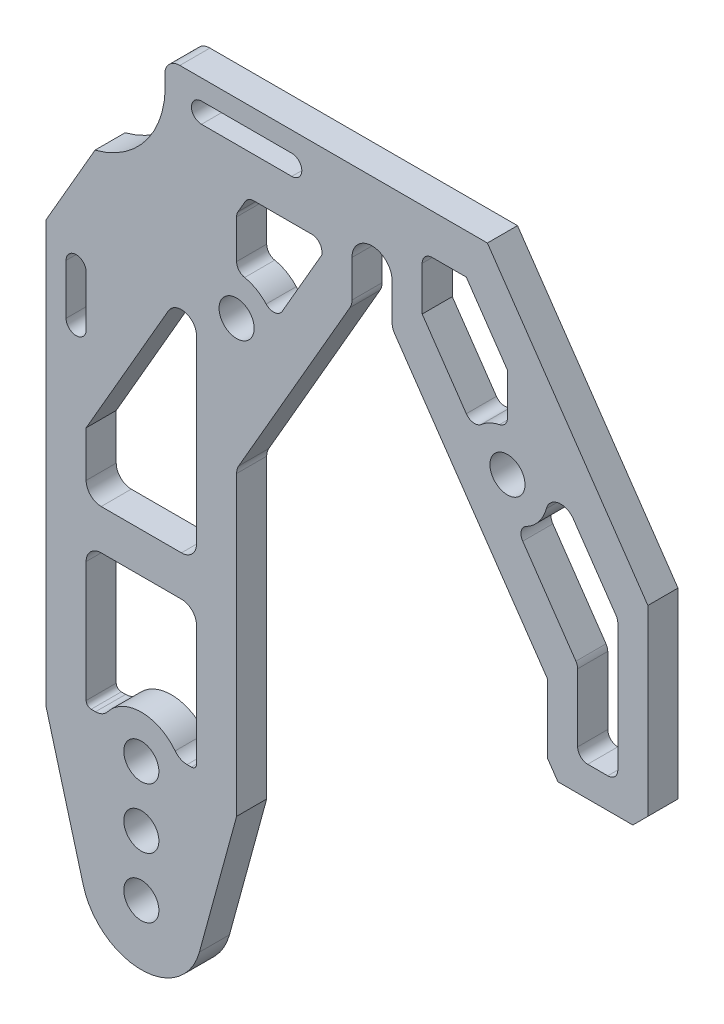
SolidWorks part; units mm, degrees
ref_plane "Plano frontal" through (0, 0, 0) normal (0, 0, 1) x (1, 0, 0)
ref_plane "Plano superior" through (0, 0, 0) normal (0, 1, 0) x (1, 0, 0)
ref_plane "Plano direito" through (0, 0, 0) normal (1, 0, 0) x (0, 0, -1)
sketch "Esboço1" plane through (0, 0, 0) normal (0, 0, 1) x (1, 0, 0)
  line L0 (23.094, 160) -> (88, 160)
  line L3 (100, 142.5303) -> (100, 114)
  line L4 (100, 114) -> (84, 114)
  line L5 (84, 114) -> (69, 135.8372)
  line L6 (69, 135.8372) -> (69, 144)
  line L7 (61, 144) -> (61, 135.8372)
  line L8 (61, 135.8372) -> (38, 96)
  line L9 (38, 96) -> (38, 0)
  line L13 (0, 0) -> (0, 120)
  line L14 (0, 0) -> (38, 0)
  line L15 (100, 142.5303) -> (88, 160)
  line L16 (23.094, 160) -> (0, 120)
  line L17 (19, 36) -> (19, 24) construction
  line L18 (19, 24) -> (19, 12) construction
  line L19 (19, 12) -> (19, 0) construction
  line L20 (41, 154) -> (49, 154) construction
  line L21 (41, 156) -> (49, 156)
  line L22 (41, 152) -> (49, 152)
  line L23 (6, 115) -> (6, 105) construction
  line L24 (8, 115) -> (8, 105)
  line L25 (4, 115) -> (4, 105)
  arc A1 (69, 144) -> (61, 144) centre (65, 144) ccw
  circle A2 centre (19, 12) radius 3.5
  circle A3 centre (19, 24) radius 3.5
  circle A4 centre (19, 36) radius 3.5
  arc A5 (41, 156) -> (41, 152) centre (41, 154) ccw
  arc A6 (49, 152) -> (49, 156) centre (49, 154) ccw
  arc A7 (8, 115) -> (4, 115) centre (6, 115) ccw
  arc A8 (4, 105) -> (8, 105) centre (6, 105) ccw
  circle A9 centre (92, 122) radius 3.5
  circle A10 centre (38, 122) radius 3.5
  point P24 (45, 154)
  point P31 (6, 110)
  dimension "D11" = 7
  dimension "D16" = 2
  dimension "D20" = 2
  dimension "D23" = 7
  dimension "D24" = 8
  dimension "D25" = 8
  dimension "D26" = 7
  dimension "D1" = 160
  dimension "D2" = 100
  dimension "D3" = 8
  dimension "D4" = 46
  dimension "D5" = 16
  dimension "D6" = 35
  dimension "D7" = 16
  dimension "D8" = 46
  dimension "D9" = 150
  dimension "D10" = 12
  dimension "D12" = 96
  dimension "D13" = 120
  dimension "D14" = 12
  dimension "D15" = 6
  dimension "D17" = 20
  dimension "D18" = 8
  dimension "D19" = 6
  dimension "D21" = 10
  dimension "D22" = 110
extrude "Ressalto-extrusão1" add sketch "Esboço1" along normal blind 6
fillet "Filete1" radius 3 5 edges at (38, 96, 3) (61, 135.8372, 3) (69, 135.8372, 3) (84, 114, 3) (100, 114, 3)
chamfer "Chanfro1" distance 2 angle 45 2 edges at (0, 0, 3) (38, 0, 3)
sketch "Esboço2" plane through (0, 0, 6) normal (0, 0, 1) x (1, 0, 0)
  line L0 (75, 152) -> (75, 141.2317)
  line L1 (75, 141.2317) -> (85.2552, 126.3021)
  line L2 (92, 130) -> (92, 140.0473)
  line L3 (92, 140.0473) -> (83.7897, 152)
  line L4 (83.7897, 152) -> (75, 152)
  line L11 (69.5272, 135.0697) -> (83.1061, 115.3014) construction
  line L12 (100, 142.5303) -> (88, 160) construction
  line L13 (88, 160) -> (23.094, 160) construction
  line L14 (100, 117) -> (100, 142.5303) construction
  line L15 (69, 144) -> (69, 136.7683) construction
  line L16 (65, 140) -> (65, 160) construction
  line L19 (38, 130) -> (38, 140.0473)
  line L20 (55, 141.4449) -> (45.4526, 124.9083)
  line L21 (55, 144) -> (55, 141.4449)
  line L22 (38, 140.0473) -> (40.2821, 144)
  line L23 (40.2821, 144) -> (55, 144)
  line L24 (41, 152) -> (49, 152) construction
  line L25 (38.4019, 96.6962) -> (60.5981, 135.141) construction
  line L26 (61, 136.641) -> (61, 144) construction
  arc A4 (92, 130) -> (85.2552, 126.3021) centre (92, 122) ccw
  arc A5 (69, 144) -> (61, 144) centre (65, 144) ccw construction
  arc A6 (38, 130) -> (45.4526, 124.9083) centre (38, 122) cw
  dimension "D6" = 8
  dimension "D1" = 8
  dimension "D2" = 8
  dimension "D3" = 8
  dimension "D4" = 8
  dimension "D5" = 6
  dimension "D7" = 8
  dimension "D8" = 8
  dimension "D9" = 6
extrude "Corte-extrusão1" cut sketch "Esboço2" against normal blind 6
sketch "Esboço3" plane through (0, 0, 6) normal (0, 0, 1) x (1, 0, 0)
  line L0 (100, 142.5303) -> (120, 113.414)
  line L1 (100, 117) -> (100, 142.5303) construction
  line L2 (100, 142.5303) -> (88, 160) construction
  line L3 (83.1061, 115.3014) -> (100, 90.707)
  line L4 (69.5272, 135.0697) -> (83.1061, 115.3014) construction
  line L5 (120, 113.414) -> (120, 77)
  line L6 (100, 90.707) -> (100, 77)
  line L7 (100, 77) -> (102.0607, 74)
  line L8 (102.0607, 74) -> (117, 74)
  line L9 (117, 74) -> (120, 77)
  line L10 (85.5789, 114) -> (97, 114) construction
  line L11 (83.1061, 115.3014) -> (100, 117)
  line L12 (100, 117) -> (100, 142.5303)
  dimension "D1" = 20
  dimension "D2" = 40
  dimension "D3" = 20
  dimension "D4" = 3
  dimension "D5" = 3
  dimension "D6" = 3
extrude "Ressalto-extrusão2" add sketch "Esboço3" against normal through all
sketch "Esboço4" plane through (0, 0, 6) normal (0, 0, 1) x (1, 0, 0)
  line L0 (105.1223, 120.9438) -> (114, 108.0195)
  line L1 (114, 108.0195) -> (114, 80)
  line L2 (114, 80) -> (106, 80)
  line L3 (106, 80) -> (106, 96.1016)
  line L5 (93.5952, 114.1607) -> (106, 96.1016)
  line L6 (75, 141.2317) -> (85.2552, 126.3021) construction
  line L7 (102.0607, 74) -> (117, 74) construction
  line L8 (100, 90.707) -> (100, 77) construction
  line L9 (120, 77) -> (120, 113.414) construction
  line L10 (92, 140.0473) -> (83.7897, 152) construction
  arc A0 (93.5952, 114.1607) -> (99.7451, 119.9965) centre (92, 122) ccw
  arc A1 (99.7451, 119.9965) -> (105.1223, 120.9438) centre (102.6495, 119.2452) cw
  dimension "D5" = 3
  dimension "D1" = 6
  dimension "D2" = 6
  dimension "D3" = 6
extrude "Corte-extrusão2" cut sketch "Esboço4" against normal blind 10
fillet "Filete2" radius 2 13 edges at (93.5952, 114.1607, 3) (114, 80, 3) (106, 80, 3) (75, 152, 3) (45.4526, 124.9083, 3) (38, 130, 3) (85.2552, 126.3021, 3) (38, 140.0473, 3) (40.2821, 144, 3) (55, 144, 3) (114, 108.0195, 3) (106, 96.1016, 3) (92, 130, 3)
sketch "Esboço5" plane through (0, 0, 6) normal (0, 0, 1) x (1, 0, 0)
  line L0 (30, 114.9948) -> (30, 79)
  line L1 (27, 76) -> (11, 76)
  line L2 (8, 79) -> (8, 88.0858)
  line L5 (8, 88.0858) -> (24.4019, 116.4948)
  line L6 (39.7047, 143) -> (38.2679, 140.5114) construction
  line L7 (38, 2) -> (38, 95.1962) construction
  line L8 (0, 120) -> (0, 2) construction
  line L9 (11, 68) -> (27, 68)
  line L10 (30, 65) -> (30, 41)
  line L11 (8, 65) -> (8, 41)
  line L12 (9, 40) -> (9.8759, 40)
  line L13 (28.1241, 40) -> (29, 40)
  line L14 (2, 0) -> (36, 0) construction
  line L15 (7.4246, 8.8361) -> (0, 36)
  line L16 (0, 36) -> (0, 0)
  line L17 (0, 0) -> (38, 0)
  line L18 (38, 0) -> (38, 36)
  line L19 (38, 36) -> (30.5754, 8.8361)
  arc A0 (12.2561, 41.1739) -> (25.7439, 41.1739) centre (19, 36) cw
  arc A1 (30, 114.9948) -> (24.4019, 116.4948) centre (27, 114.9948) ccw
  circle A2 centre (19, 36) radius 3.5 construction
  arc A3 (8, 79) -> (11, 76) centre (11, 79) ccw
  arc A4 (30, 79) -> (27, 76) centre (27, 79) cw
  arc A5 (8, 65) -> (11, 68) centre (11, 65) cw
  arc A6 (28.1241, 40) -> (25.7439, 41.1739) centre (28.1241, 43) cw
  arc A7 (9.8759, 40) -> (12.2561, 41.1739) centre (9.8759, 43) ccw
  arc A8 (30, 41) -> (29, 40) centre (29, 41) cw
  arc A9 (9, 40) -> (8, 41) centre (9, 41) cw
  arc A10 (30, 65) -> (27, 68) centre (27, 65) ccw
  arc A11 (7.4246, 8.8361) -> (30.5754, 8.8361) centre (19, 12) ccw
  point P30 (8, 68)
  point P39 (8, 40)
  dimension "D4" = 8.5
  dimension "D7" = 3
  dimension "D8" = 3
  dimension "D9" = 3
  dimension "D10" = 3
  dimension "D11" = 3
  dimension "D12" = 3
  dimension "D13" = 1
  dimension "D14" = 3
  dimension "D1" = 8
  dimension "D2" = 8
  dimension "D3" = 8
  dimension "D5" = 4
  dimension "D6" = 28
extrude "Corte-extrusão3" cut sketch "Esboço5" against normal blind 10 contours A11 L15 L16 L17 | A11 L17 L18 L19 | L10 A10 L9 A5 L11 A9 L12 A7 A0 A6 L13 A8 | A4 L0 A1 L5 L2 A3 L1
sketch "Esboço6" plane through (0, 0, 6) normal (0, 0, 1) x (1, 0, 0)
  line L0 (31, 154) -> (49, 154) construction
  line L1 (31, 156) -> (49, 156)
  line L2 (31, 152) -> (49, 152)
  line L3 (49, 156) -> (41, 156) construction
  arc A0 (31, 156) -> (31, 152) centre (31, 154) ccw
  arc A1 (49, 152) -> (49, 156) centre (49, 154) ccw
  point P3 (40, 154)
  dimension "D1" = 18
extrude "Corte-extrusão4" cut sketch "Esboço6" against normal through all
sketch "Esboço7" plane through (0, 0, 6) normal (0, 0, 1) x (1, 0, 0)
  line L0 (23.094, 160) -> (0, 120) construction
  line L1 (23.094, 160) -> (9.77, 136.9222)
  arc A0 (23.094, 160) -> (9.77, 136.9222) centre (5.0924, 155.008) cw
extrude "Corte-extrusão5" cut sketch "Esboço7" against normal through all
fillet "Filete3" radius 3 1 edges at (23.094, 160, 3)
